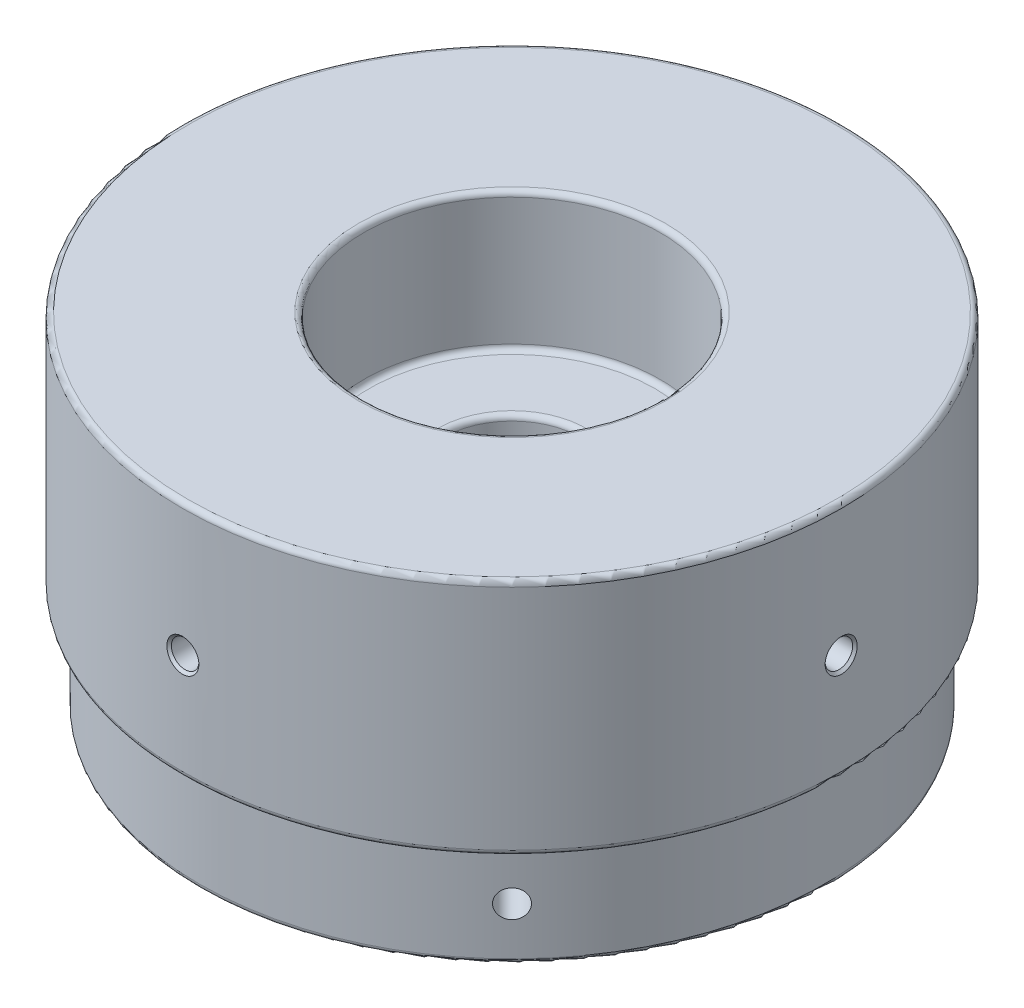
SolidWorks part; units mm, degrees
material "Delrin 2700 NC010, Düşük Viskozite Asetal Kopolimer (SS)"
ref_plane "Ön Düzlem" through (0, 0, 0) normal (0, 0, 1) x (1, 0, 0)
ref_plane "Üst Düzlem" through (0, 0, 0) normal (0, 1, 0) x (1, 0, 0)
ref_plane "Sağ Düzlem" through (0, 0, 0) normal (1, 0, 0) x (0, 0, -1)
sketch "Çizim1" plane through (0, 0, 0) normal (0, 1, 0) x (1, 0, 0)
  circle A0 centre (0, 0) radius 62.2
  dimension "D1" = 124.4
extrude "Yükseklik-Ekstrüzyon1" add sketch "Çizim1" along normal mid plane 65
sketch "Çizim2" plane through (0, 32.5, 0) normal (0, 1, 0) x (1, 0, 0)
  circle A0 centre (0, 0) radius 28
  dimension "D1" = 56
extrude "Kes-Ekstrüzyon1" cut sketch "Çizim2" against normal blind 26
sketch "Çizim3" plane through (0, 6.5, 0) normal (0, 1, 0) x (1, 0, 0)
  circle A0 centre (0, 0) radius 13
  dimension "D1" = 26
extrude "Kes-Ekstrüzyon2" cut sketch "Çizim3" against normal blind 20
sketch "Çizim4" plane through (0, -32.5, 0) normal (0, -1, 0) x (1, 0, 0)
  circle A0 centre (0, 0) radius 59
  circle A1 centre (0, 0) radius 62.2
  dimension "D1" = 118
  dimension "D2" = 124.4
extrude "Kes-Ekstrüzyon3" cut sketch "Çizim4" against normal blind 20
sketch "Çizim6" plane through (0, 32.5, 0) normal (0, 1, 0) x (1, 0, 0)
  line L0 (0, 0) -> (62.2, 0) construction
  line L1 (62.2, -12.4881) -> (62.2, 12.4881) construction
  circle A0 centre (0, 0) radius 62.2 construction
  point P8 (62.2, 0)
sketch "Çizim7" plane through (0, -12.5, 0) normal (0, -1, 0) x (1, 0, 0)
  line L0 (0, 0) -> (62.2, 0) construction
  line L1 (0, 0) -> (41.7193, 41.7193) construction
  line L2 (52.9586, 28.3587) -> (30.48, 55.0799) construction
  circle A0 centre (0, 0) radius 59 construction
  point P10 (41.7193, 41.7193)
  dimension "D1" = 45
ref_plane "Düzlem1" through (62.2, 0, 0) normal (-1, 0, 0) x (0, 0, 1)
sketch "Çizim8" plane through (62.2, 0, 0) normal (-1, 0, 0) x (0, 0, 1)
  line L0 (0, 32.5) -> (0, 7.5) construction
  point P1 (0, 7.5)
  point P8 (0, 7.5)
  dimension "D1" = 25
hole_wizard "M5x0.8 Helisarmal İçin Dişli Delik2" positions "Çizim8" profile "Çizim9" tap size "M5x0.8" standard "Helicoil® Metric"
sketch "Çizim9" plane through (62.2, 7.5, 0) normal (0, 1, 0) x (0, 0, -1)
  line L0 (0, 0) -> (0, 13.8622)
  line L1 (0, 13.8622) -> (2.6, 12.3)
  line L2 (2.6, 12.3) -> (2.6, 0.4975)
  line L3 (2.6, 0.4975) -> (3.0975, 0)
  line L5 (3.0975, 0) -> (0, 0)
  line L6 (-2.6, 0.4975) -> (-3.0975, 0) construction
  line L10 (0, 13.8622) -> (-2.6, 12.3) construction
  line L11 (0, -6.35) -> (0, 107.95) construction
  dimension "Tap Drill Dia." = 5.2
  dimension "Tap Drill Depth" = 12.3
  dimension "Near C'Sink Dia." = 6.195
  dimension "Near C'Sink Angle" = 90
  dimension "Drill Angle" = 118
cosmetic thread "Delik Dişi1" parameters "D1"=5.8, "D2"=6.145
pattern_circular "Dairesel Kaplama1" count 4 over 360 about axis through (0, 32.5, 0) along (0, 1, 0) of "M5x0.8 Helisarmal İçin Dişli Delik2"
cosmetic thread "Delik Dişi2" parameters "D1"=5.8, "D2"=6.145
cosmetic thread "Delik Dişi3" parameters "D1"=5.8, "D2"=6.145
cosmetic thread "Delik Dişi4" parameters "D1"=5.8, "D2"=6.145
sketch "Çizim21" plane through (0, -32.5, 0) normal (0, -1, 0) x (1, 0, 0)
  line L0 (0, 0) -> (41.7193, 41.7193) construction
  line L1 (0, 0) -> (18.9326, 0) construction
  circle A0 centre (0, 0) radius 59 construction
  dimension "D1" = 45
sketch "Çizim22" plane through (0, -12.5, 0) normal (0, -1, 0) x (1, 0, 0)
  line L0 (0, 0) -> (41.7193, 41.7193) construction
  line L1 (34.9404, 48.4982) -> (48.4982, 34.9404) construction
  point P9 (41.7193, 41.7193)
  point P10 (41.7193, 41.7193)
  point P13 (41.7193, 41.7193)
ref_plane "Düzlem5" through (41.7193, 0, 41.7193) normal (-0.7071, 0, -0.7071) x (-0.7071, 0, 0.7071)
sketch "Çizim23" plane through (41.7193, 0, 41.7193) normal (-0.7071, 0, -0.7071) x (-0.7071, 0, 0.7071)
  line L0 (0, -32.5) -> (0, -22.5) construction
  line L1 (0, -32.5) -> (-13.3874, -32.5) construction
  point P1 (0, -22.5)
  point P8 (0, -22.5)
  dimension "D1" = 10
hole_wizard "M5x0.8 Helisarmal İçin Dişli Delik6" positions "Çizim23" profile "Çizim24" tap size "M5x0.8" standard "Helicoil® Metric"
sketch "Çizim24" plane through (41.7193, -22.5, 41.7193) normal (0, 1, 0) x (0.7071, 0, -0.7071)
  line L0 (0, 0) -> (0, 9.8622)
  line L1 (0, 9.8622) -> (2.6, 8.3)
  line L2 (2.6, 8.3) -> (2.6, 0)
  line L5 (2.6, 0) -> (0, 0)
  line L10 (0, 9.8622) -> (-2.6, 8.3) construction
  line L11 (0, -6.35) -> (0, 107.95) construction
  dimension "Tap Drill Dia." = 5.2
  dimension "Tap Drill Depth" = 8.3
  dimension "Drill Angle" = 118
cosmetic thread "Delik Dişi12" parameters "D1"=5.8, "D2"=6.145
pattern_circular "Dairesel Kaplama3" count 4 over 360 about axis through (0, -32.5, 0) along (0, -1, 0) of "M5x0.8 Helisarmal İçin Dişli Delik6"
cosmetic thread "Delik Dişi13" parameters "D1"=5.8, "D2"=6.145
cosmetic thread "Delik Dişi14" parameters "D1"=5.8, "D2"=6.145
cosmetic thread "Delik Dişi15" parameters "D1"=5.8, "D2"=6.145
fillet "Radyus2" radius 1 7 edges at (0, -13.5, 13) (0, 6.5, 13) (0, 6.5, 28) (0, 32.5, 28) (0, -32.5, -59) (0, -12.5, -62.2) (0, 32.5, 62.2)
sketch "Çizim25" plane through (0, -32.5, 0) normal (0, -1, 0) x (1, 0, 0)
  point P0 (0, 0)
hole_wizard "M8x1.0 Helisarmal İçin Dişli Delik3" positions "Çizim25" profile "Çizim26" tap size "M8x1.0" standard "Helicoil® Metric" end condition through all
sketch "Çizim26" plane through (0, -32.5, 0) normal (1, 0, 0) x (0, 0, -1)
  line L0 (0, 0) -> (0, 65)
  line L1 (0, 65) -> (4.125, 65)
  line L2 (4.125, 65) -> (4.125, 0)
  line L5 (4.125, 0) -> (0, 0)
  line L11 (0, -6.35) -> (0, 107.95) construction
  dimension "Thru Tap Drill Dia." = 8.25
  dimension "Thru Tap Drill Depth" = 65
cosmetic thread "Delik Dişi16" parameters "D1"=9, "D2"=9.422
